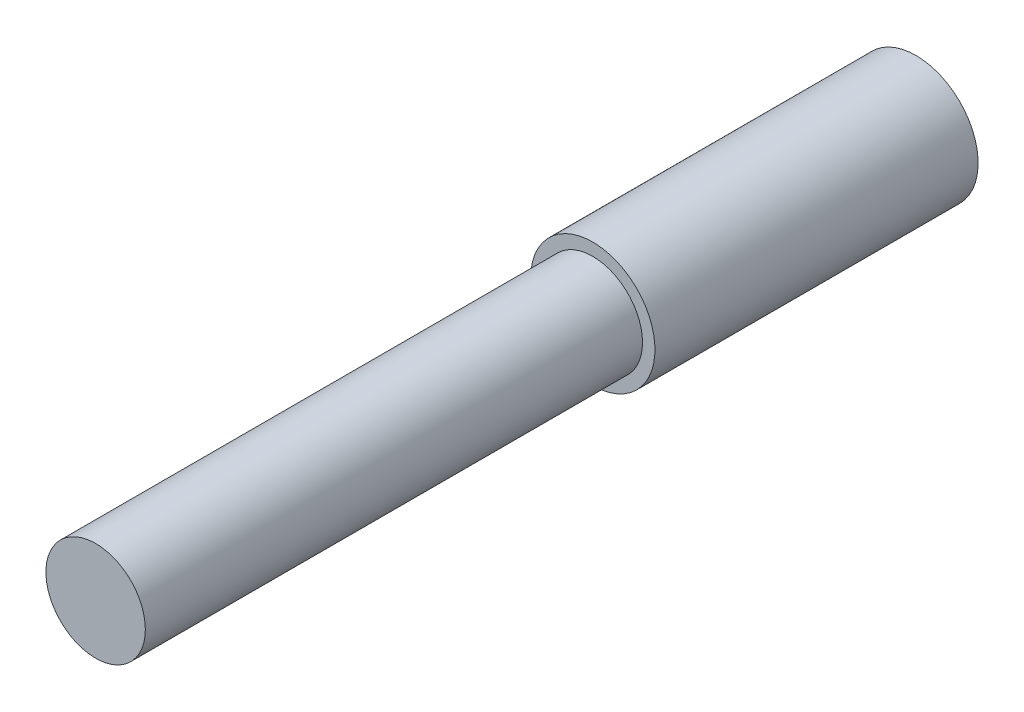
SolidWorks part; units mm, degrees
ref_plane "Front Plane" through (0, 0, 0) normal (0, 0, 1) x (1, 0, 0)
ref_plane "Top Plane" through (0, 0, 0) normal (0, 1, 0) x (1, 0, 0)
ref_plane "Right Plane" through (0, 0, 0) normal (1, 0, 0) x (0, 0, -1)
sketch "Sketch1" plane through (0, 0, 0) normal (0, 0, 1) x (1, 0, 0)
  circle A0 centre (0, 0) radius 2.5
  dimension "D1" = 5
extrude "Boss-Extrude2" add sketch "Sketch1" along normal blind 13
sketch "Sketch2" plane through (0, 0, 13) normal (0, 0, 1) x (1, 0, 0)
  circle A0 centre (0, 0) radius 2
  dimension "D1" = 4
extrude "Boss-Extrude3" add sketch "Sketch2" along normal blind 20
